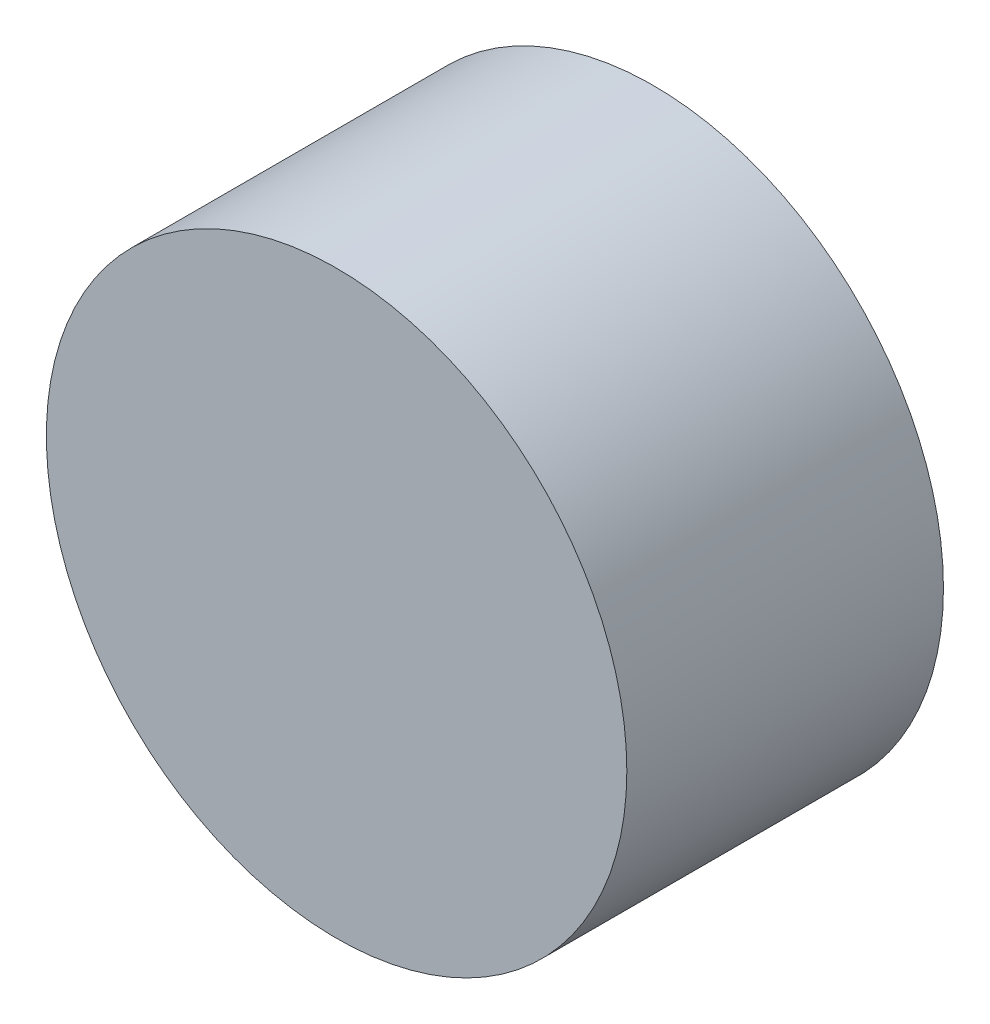
SolidWorks part; units mm, degrees
ref_plane "Front Plane" through (0, 0, 0) normal (0, 0, 1) x (1, 0, 0)
ref_plane "Top Plane" through (0, 0, 0) normal (0, 1, 0) x (1, 0, 0)
ref_plane "Right Plane" through (0, 0, 0) normal (1, 0, 0) x (0, 0, -1)
sketch "Esquisse1" plane through (0, 0, 0) normal (0, 0, 1) x (1, 0, 0)
  circle A0 centre (0, 0) radius 55
  dimension "D1" = 110
extrude "Boss.-Extru.1" add sketch "Esquisse1" along normal blind 60
